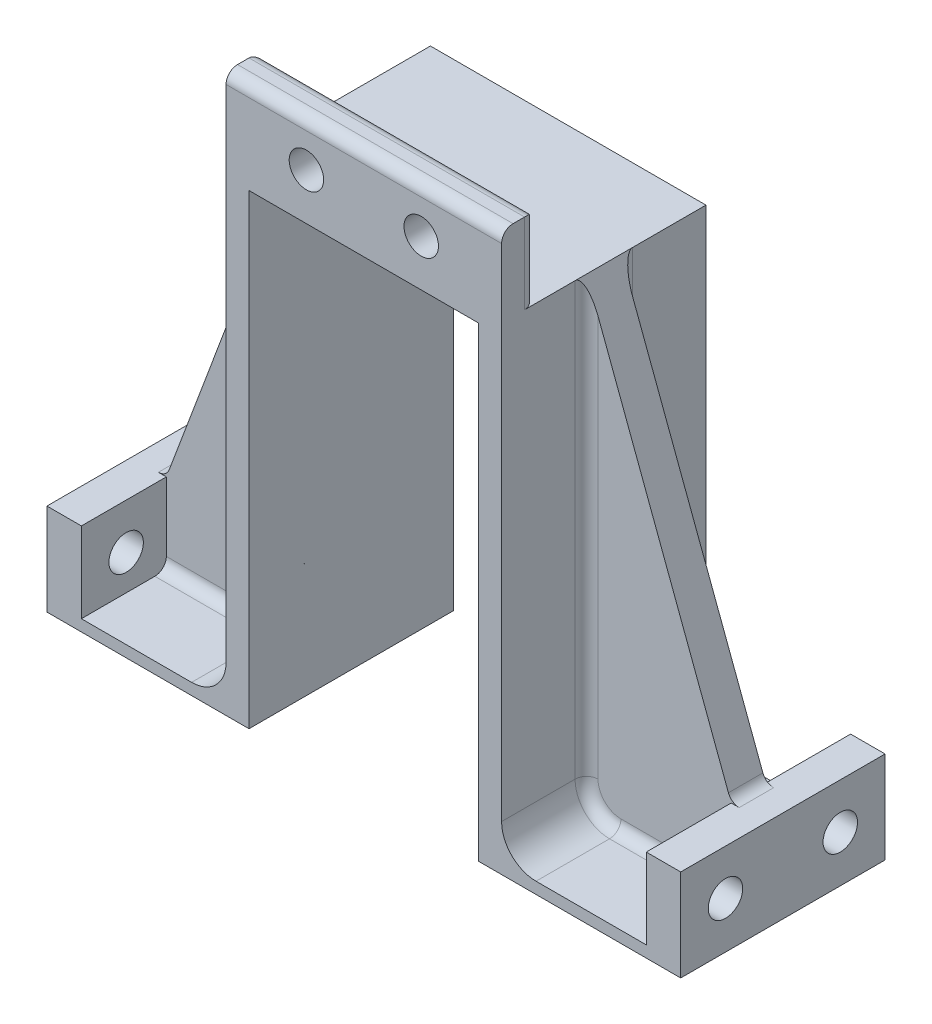
SolidWorks part; units mm, degrees
ref_plane "Front Plane" through (0, 0, 0) normal (0, 0, 1) x (1, 0, 0)
ref_plane "Top Plane" through (0, 0, 0) normal (0, 1, 0) x (1, 0, 0)
ref_plane "Right Plane" through (0, 0, 0) normal (1, 0, 0) x (0, 0, -1)
sketch "Sketch1" plane through (0, 0, 0) normal (0, 0, 1) x (1, 0, 0)
  line L0 (0, -2.717) -> (0, 26.0552) construction
  line L5 (-10, 0) -> (10, 0)
  line L6 (10, 0) -> (10, -40.6)
  line L7 (-12, 1) -> (12, 1)
  line L8 (12, 1) -> (12, -39.6)
  line L9 (-12, 1) -> (-12, -39.6)
  line L10 (-10, 0) -> (-10, -40.6)
  line L11 (-10, -40.6) -> (-27.6, -40.6)
  line L12 (-12, -39.6) -> (-27.6, -39.6)
  line L13 (12, -39.6) -> (27.6, -39.6)
  line L14 (10, -40.6) -> (27.6, -40.6)
  line L15 (-27.6, -39.6) -> (-27.6, -40.6)
  line L16 (27.6, -39.6) -> (27.6, -40.6)
  point P5 (0, 0)
  point P9 (0, 1)
  dimension "D1" = 20
  dimension "D2" = 1
  dimension "D3" = 2
  dimension "D4" = 2
  dimension "D5" = 1
  dimension "D6" = 17.6
  dimension "D7" = 40.6
extrude "Boss-Extrude1" add sketch "Sketch1" along normal mid plane 17.8
sketch "Sketch5" plane through (0, 0, 0) normal (0, 0, 1) x (1, 0, 0)
  line L0 (-12, -39.6) -> (-27.6, -39.6) construction
  line L1 (-12, -39.6) -> (-27.6, -39.6)
  line L2 (-27.6, -39.6) -> (-27.6, -32.6)
  line L3 (-27.6, -32.6) -> (-24.6, -32.6)
  line L4 (-24.6, -32.6) -> (-24.6, -39.6)
  line L5 (0, 0) -> (0, -39.3866) construction
  line L6 (12, -39.6) -> (27.6, -39.6)
  line L7 (24.6, -32.6) -> (24.6, -39.6)
  line L8 (27.6, -32.6) -> (24.6, -32.6)
  line L9 (27.6, -39.6) -> (27.6, -32.6)
  dimension "D1" = 3
  dimension "D2" = 7
extrude "Boss-Extrude3" add sketch "Sketch5" along normal up to surface and the other way up to surface contours L4 L3 L2 L1 | L6 L9 L8 L7
sketch "Sketch6" plane through (0, 0, 0) normal (0, 0, 1) x (1, 0, 0)
  line L2 (-12, 1) -> (-12, -39.6) construction
  line L3 (-24.6, -32.6) -> (-24.6, -39.6) construction
  line L4 (-12, 1) -> (-12, -39.6) construction
  line L5 (-24.6, -32.6) -> (-24.6, -39.6) construction
  line L6 (-24.6, -32.6) -> (-12, 1)
  dimension "D1" = 40.6
sketch "Sketch7" plane through (-27.6, 0, 0) normal (-1, 0, 0) x (0, 0, 1)
  line L0 (0, -40.6) -> (0, -36.55) construction
  line L1 (8.9, -40.6) -> (-8.9, -40.6) construction
  line L2 (8.9, -40.6) -> (-8.9, -40.6) construction
  line L3 (-5, -36.55) -> (5, -36.55) construction
  line L4 (8.9, -32.6) -> (-8.9, -32.6)
  line L5 (-8.9, -32.6) -> (-8.9, -40.6)
  line L6 (-8.9, -40.6) -> (8.9, -40.6)
  line L7 (8.9, -40.6) -> (8.9, -32.6)
  line L8 (8.9, -32.6) -> (-8.9, -32.6) construction
  line L9 (-8.9, -32.6) -> (-8.9, -40.6) construction
  line L11 (8.9, -40.6) -> (8.9, -32.6) construction
  circle A0 centre (-5, -36.55) radius 1.5
  circle A1 centre (5, -36.55) radius 1.5
  point P9 (0, -36.55)
  dimension "D4" = 3
  dimension "D2" = 4.05
  dimension "D3" = 10
  dimension "D1" = 0
sketch "Sketch9" plane through (0, 0, 8.9) normal (0, 0, 1) x (1, 0, 0)
  line L0 (12, 1) -> (-12, 1) construction
  line L1 (12, 1) -> (-12, 1)
  line L2 (-12, 1) -> (-12, 8)
  line L3 (-12, 8) -> (12, 8)
  line L4 (12, 8) -> (12, 1)
  line L5 (0, 0) -> (0, 4.05) construction
  line L6 (-5, 4.05) -> (5, 4.05) construction
  circle A0 centre (-5, 4.05) radius 1.5
  circle A1 centre (5, 4.05) radius 1.5
  point P10 (0, 4.05)
  dimension "D4" = 3
  dimension "D1" = 7
  dimension "D2" = 4.05
  dimension "D3" = 10
extrude "Boss-Extrude4" add sketch "Sketch9" against normal blind 3
rib "Rib2" sketch "Sketch6" sketch "Sketch6" thickness 3 extrusion direction parallel to sketch draft on no parameters "D1"=3
mirror "Mirror3" about plane through (0, 0, 0) normal (1, 0, 0) of "Rib2"
extrude "Cut-Extrude2" cut sketch "Sketch7" against normal blind 3
mirror "Mirror4" about plane through (0, 0, 0) normal (1, 0, 0) of "Cut-Extrude2"
fillet "Fillet1" radius 3 2 edges at (-12, -39.6, -5.2) (12, -39.6, -5.2)
fillet "Fillet2" radius 1 18 edges at (-12, -17.8, 1.5) (-12, -17.8, -1.5) (24.6, -32.6, 0) (19.8, -39.6, -1.5) (19.8, -39.6, 1.5) (-19.8, -39.6, -1.5) (-12.8787, -38.7213, -1.5) (-19.8, -39.6, 1.5) (-12.8787, -38.7213, 1.5) (12, -17.8, 1.5) (12.8787, -38.7213, 1.5) (12, -17.8, -1.5) (12.8787, -38.7213, -1.5) (12, 4.5, 5.9) (-12, 4.5, 5.9) (0, 8, 5.9) (0, 8, 8.9) (-24.6, -32.6, 0)
